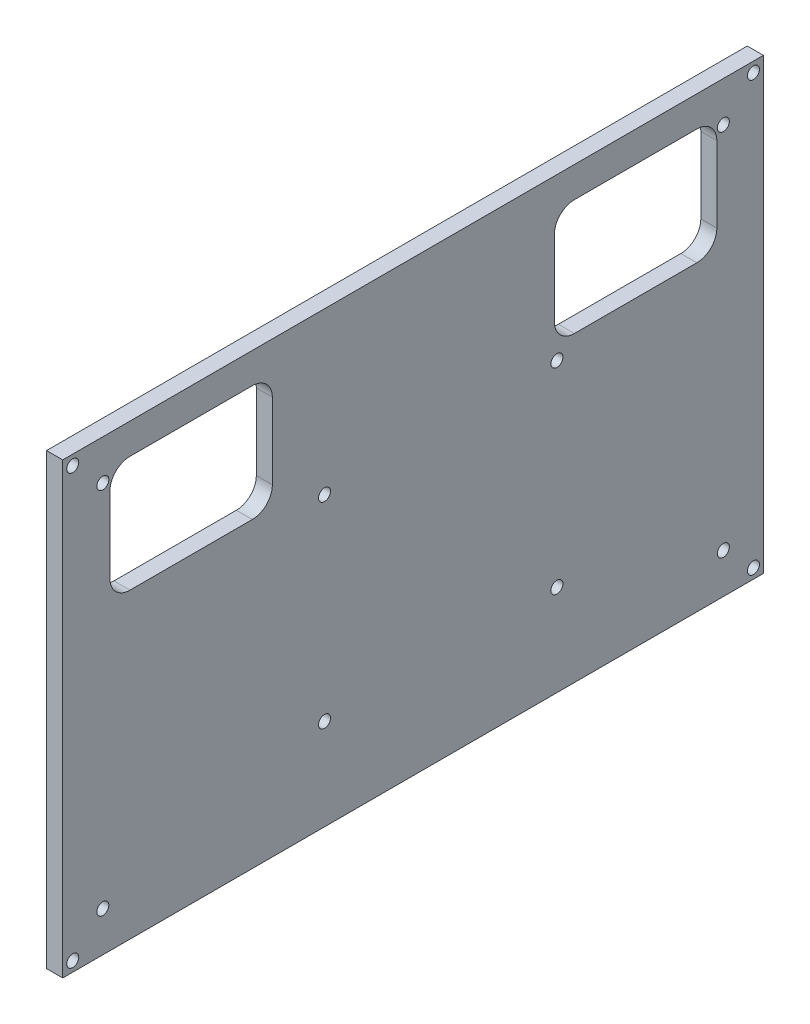
SolidWorks part; units mm, degrees
ref_plane "Alzado" through (0, 0, 0) normal (0, 0, 1) x (1, 0, 0)
ref_plane "Planta" through (0, 0, 0) normal (0, 1, 0) x (1, 0, 0)
ref_plane "Vista lateral" through (0, 0, 0) normal (1, 0, 0) x (0, 0, -1)
sketch "Croquis1" plane through (0, 0, 0) normal (1, 0, 0) x (0, 0, -1)
  line L1 (82.45, -51) -> (-82.45, -51)
  line L2 (82.45, -51) -> (82.45, 51)
  line L3 (82.45, 51) -> (-82.45, 51)
  line L4 (-82.45, -51) -> (-82.45, 51)
  point P0 (0, 0)
  point P5 (0, 0)
  dimension "D1" = 102
  dimension "D2" = 164.9
extrude "Saliente-Extruir2" add sketch "Croquis1" along normal blind 14.27
sketch "Croquis2" plane through (0, 0, 0) normal (1, 0, 0) x (0, 0, -1)
  line L0 (82.45, -51) -> (82.45, 51) construction
  line L5 (87.45, 56) -> (-87.45, 56)
  line L6 (87.45, 56) -> (87.45, -56)
  line L7 (87.45, -56) -> (-87.45, -56)
  line L8 (-87.45, 56) -> (-87.45, -56)
  line L9 (-82.45, 51) -> (-82.45, -51) construction
  line L10 (82.45, 51) -> (-82.45, 51) construction
  line L11 (-82.45, -51) -> (82.45, -51) construction
  line L13 (83.45, 52) -> (-83.45, 52)
  line L14 (83.45, 52) -> (83.45, -52)
  line L15 (83.45, -52) -> (-83.45, -52)
  line L16 (-83.45, 52) -> (-83.45, -52)
  dimension "D1" = 5
  dimension "D2" = 5
  dimension "D3" = 5
  dimension "D4" = 5
  dimension "D5" = 1
  dimension "D6" = 1
  dimension "D7" = 1
  dimension "D8" = 1
extrude "Saliente-Extruir3" add sketch "Croquis2" along normal blind 14.27 separate body
sketch "Croquis3" plane through (0, 0, 0) normal (-1, 0, 0) x (0, 0, 1)
  line L0 (83.45, 52) -> (83.45, -52) construction
  line L1 (-87.45, 56) -> (87.45, 56)
  line L2 (-87.45, 56) -> (-87.45, -56)
  line L3 (-87.45, -56) -> (87.45, -56)
  line L4 (87.45, 56) -> (87.45, -56)
  line L5 (-80.45, 49.125) -> (80.45, 49.125)
  line L6 (-80.45, 49.125) -> (-80.45, -49.2494)
  line L7 (-80.45, -49.2494) -> (80.45, -49.2494)
  line L8 (80.45, 49.125) -> (80.45, -49.2494)
  line L9 (-83.45, -52) -> (-83.45, 52) construction
  line L10 (-83.45, 52) -> (83.45, 52) construction
  line L11 (83.45, -52) -> (-83.45, -52) construction
  dimension "D1" = 160.9
  dimension "D2" = 3
  dimension "D3" = 3
  dimension "D4" = 2.875
  dimension "D5" = 2.7506
extrude "Saliente-Extruir5" add sketch "Croquis3" along normal blind 1
sketch "Croquis4" plane through (14.27, 0, 0) normal (1, 0, 0) x (0, 0, -1)
  line L1 (-82.45, 51) -> (82.45, 51)
  line L2 (-82.45, 51) -> (-82.45, -51)
  line L3 (-82.45, -51) -> (82.45, -51)
  line L4 (82.45, 51) -> (82.45, -51)
extrude "Cortar-Extruir2" cut sketch "Croquis4" against normal blind 14.27
sketch "Croquis6" plane through (14.27, 0, 0) normal (1, 0, 0) x (0, 0, -1)
  line L1 (-87.45, 56) -> (87.45, 56)
  line L2 (-87.45, 56) -> (-87.45, -56)
  line L3 (-87.45, -56) -> (87.45, -56)
  line L4 (87.45, 56) -> (87.45, -56)
  circle A0 centre (-77.445, 46) radius 1.5
  circle A1 centre (-77.445, -46) radius 1.5
  circle A2 centre (-22.1, 15.81) radius 1.5
  circle A3 centre (35.9, 15.81) radius 1.5
  circle A4 centre (-22.1, -33.19) radius 1.5
  circle A5 centre (35.9, -33.19) radius 1.5
  circle A6 centre (77.445, 46) radius 1.5
  circle A7 centre (77.445, -46) radius 1.5
  dimension "D1" = 3
  dimension "D2" = 3
extrude "Saliente-Extruir6" add sketch "Croquis6" along normal blind 15
sketch "Croquis8" plane through (14.27, 0, 0) normal (-1, 0, 0) x (0, 0, 1)
  line L1 (-80.45, 49.125) -> (80.45, 49.125)
  line L2 (-80.45, 49.125) -> (-80.45, -49.2494)
  line L3 (-80.45, -49.2494) -> (80.45, -49.2494)
  line L4 (80.45, 49.125) -> (80.45, -49.2494)
extrude "Cortar-Extruir3" cut sketch "Croquis8" against normal blind 9
sketch "Croquis9" plane through (14.27, 0, 0) normal (-1, 0, 0) x (0, 0, 1)
  line L1 (-83.45, 52) -> (83.45, 52)
  line L2 (-83.45, 52) -> (-83.45, -52)
  line L3 (-83.45, -52) -> (83.45, -52)
  line L4 (83.45, 52) -> (83.45, -52)
extrude "Cortar-Extruir5" cut sketch "Croquis9" against normal blind 11
sketch "Croquis15" plane through (0, 0, 87.45) normal (0, 0, 1) x (1, 0, 0)
  line L0 (21.57, 16.9173) -> (15.27, 16.9173)
  line L1 (15.27, 16.9173) -> (15.27, 1.9173)
  line L2 (15.27, 1.9173) -> (21.57, 1.9173)
  line L3 (21.57, 1.9173) -> (21.57, 16.9173)
  line L4 (15.27, -7.5827) -> (18.77, -7.5827)
  line L5 (18.77, -7.5827) -> (18.77, -14.5827)
  line L6 (18.77, -14.5827) -> (15.27, -14.5827)
  line L7 (15.27, -14.5827) -> (15.27, -7.5827)
  line L8 (18.77, -25.5827) -> (18.77, -32.5827)
  line L9 (18.77, -32.5827) -> (15.27, -32.5827)
  line L10 (15.27, -32.5827) -> (15.27, -25.5827)
  line L11 (15.27, -25.5827) -> (18.77, -25.5827)
  dimension "D1" = 6.3
  dimension "D2" = 3.5
  dimension "D3" = 3.5
extrude "Cortar-Extruir6" cut sketch "Croquis15" against normal blind 7
sketch "Croquis16" plane through (29.27, 0, 0) normal (1, 0, 0) x (0, 0, -1)
  line L1 (-70.6759, 19.4509) -> (-40.1252, 19.4509)
  line L2 (-35.1252, 24.4509) -> (-35.1252, 43.3705)
  line L3 (-40.1252, 48.3705) -> (-70.6759, 48.3705)
  line L5 (-75.6759, 43.3705) -> (-75.6759, 24.4509)
  line L6 (40.2695, 19.4658) -> (70.8201, 19.4658)
  line L7 (75.8201, 24.4658) -> (75.8201, 43.3853)
  line L8 (70.8201, 48.3853) -> (40.2695, 48.3853)
  line L9 (35.2695, 43.3853) -> (35.2695, 24.4658)
  arc A0 (-40.1252, 48.3705) -> (-35.1252, 43.3705) centre (-40.1252, 43.3705) cw
  arc A1 (-35.1252, 24.4509) -> (-40.1252, 19.4509) centre (-40.1252, 24.4509) cw
  arc A2 (-75.6759, 24.4509) -> (-70.6759, 19.4509) centre (-70.6759, 24.4509) ccw
  arc A3 (-75.6759, 43.3705) -> (-70.6759, 48.3705) centre (-70.6759, 43.3705) cw
  arc A4 (70.8201, 48.3853) -> (75.8201, 43.3853) centre (70.8201, 43.3853) cw
  arc A5 (75.8201, 24.4658) -> (70.8201, 19.4658) centre (70.8201, 24.4658) cw
  arc A6 (35.2695, 24.4658) -> (40.2695, 19.4658) centre (40.2695, 24.4658) ccw
  arc A7 (35.2695, 43.3853) -> (40.2695, 48.3853) centre (40.2695, 43.3853) cw
  dimension "D1" = 5
  dimension "D2" = 5
extrude "Cortar-Extruir7" cut sketch "Croquis16" against normal blind 7
sketch "Croquis17" plane through (0, 0, -87.45) normal (0, 0, -1) x (-1, 0, 0)
  circle A0 centre (-17.7917, -27.9017) radius 4
  dimension "D1" = 8
extrude "Cortar-Extruir8" cut sketch "Croquis17" against normal blind 7
sketch "Croquis18" plane through (0, 0, -87.45) normal (0, 0, -1) x (-1, 0, 0)
  line L1 (-19.27, 4.9173) -> (-15.27, 4.9173)
  line L2 (-19.27, 4.9173) -> (-19.27, -11.0827)
  line L3 (-19.27, -11.0827) -> (-15.27, -11.0827)
  line L4 (-15.27, 4.9173) -> (-15.27, -11.0827)
extrude "Cortar-Extruir9" cut sketch "Croquis18" against normal blind 7
sketch "Croquis21" plane through (29.27, 0, 0) normal (1, 0, 0) x (0, 0, -1)
  line L0 (-87.45, 56) -> (-87.45, -56) construction
  line L1 (87.45, 56) -> (-87.45, 56) construction
  line L2 (87.45, -56) -> (87.45, 56) construction
  line L3 (-87.45, -56) -> (87.45, -56) construction
  circle A0 centre (-84.95, 53.5) radius 1.5
  circle A1 centre (84.95, 53.5) radius 1.5
  circle A2 centre (84.95, -53.5) radius 1.5
  circle A3 centre (-84.95, -53.5) radius 1.5
  dimension "D1" = 3
  dimension "D4" = 3
  dimension "D7" = 3
  dimension "D10" = 3
  dimension "D2" = 2.5
  dimension "D3" = 2.5
  dimension "D5" = 2.5
  dimension "D6" = 2.5
  dimension "D8" = 2.5
  dimension "D9" = 2.5
  dimension "D11" = 2.5
  dimension "D12" = 2.5
extrude "Cortar-Extruir12" cut sketch "Croquis21" against normal blind 25.4
sketch "Croquis22" plane through (0, 0, -87.45) normal (0, 0, -1) x (-1, 0, 0)
  line L0 (-29.27, -56) -> (1, -56) construction
  line L4 (-25.2359, 56) -> (-25.2359, -56)
  line L6 (1, 56) -> (-25.2359, 56)
  line L7 (1, 56) -> (1, -56)
  line L8 (1, -56) -> (-25.2359, -56)
extrude "Cortar-Extruir14" cut sketch "Croquis22" against normal blind 200.4
